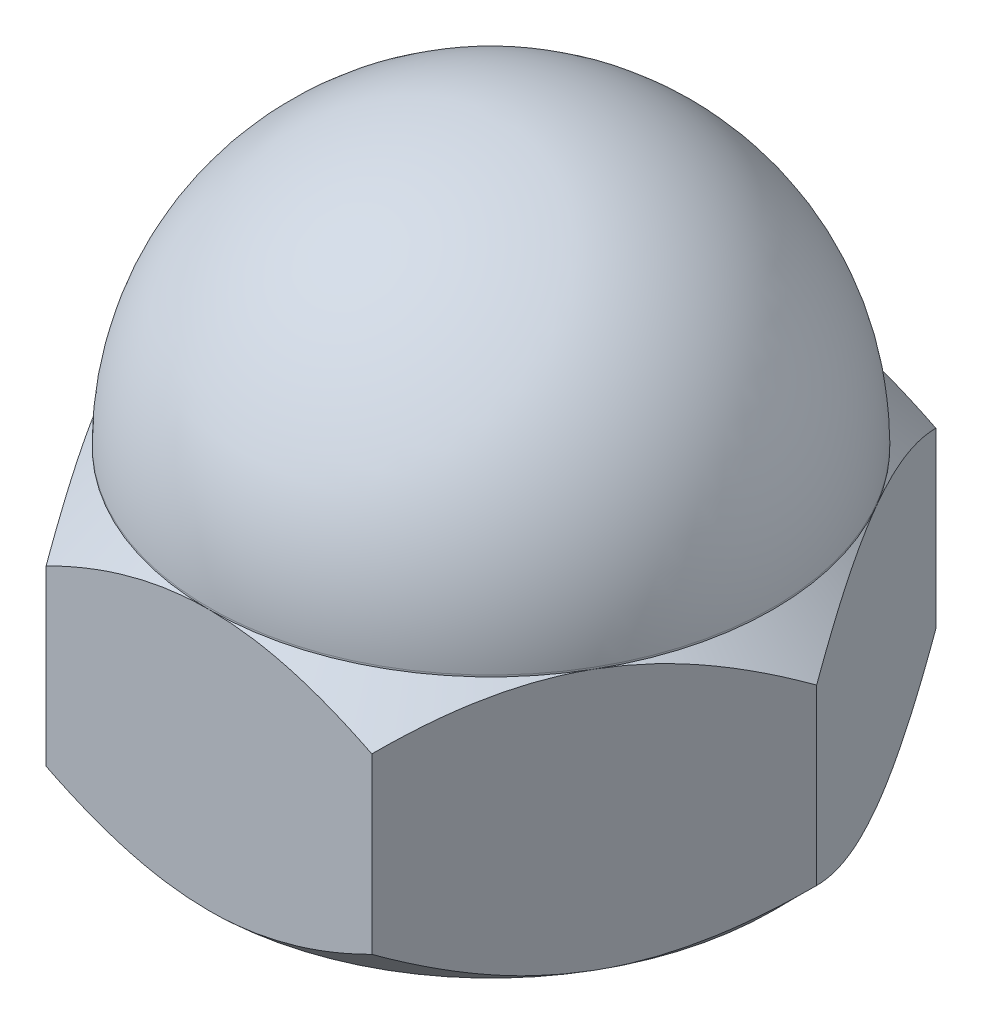
SolidWorks part; units mm, degrees
material "1023 Carbon Steel Sheet (SS)"
ref_plane "Front Plane" through (0, 0, 0) normal (0, 0, 1) x (1, 0, 0)
ref_plane "Top Plane" through (0, 0, 0) normal (0, 1, 0) x (1, 0, 0)
ref_plane "Right Plane" through (0, 0, 0) normal (1, 0, 0) x (0, 0, -1)
sketch "Sketch1" plane through (0, 0, 0) normal (0, 1, 0) x (1, 0, 0)
  line L1 (19.975, 0) -> (9.9875, 17.2989)
  line L2 (9.9875, 17.2989) -> (-9.9875, 17.2989)
  line L3 (-9.9875, 17.2989) -> (-19.975, 0)
  line L4 (-19.975, 0) -> (-9.9875, -17.2989)
  line L5 (-9.9875, -17.2989) -> (9.9875, -17.2989)
  line L6 (9.9875, -17.2989) -> (19.975, 0)
  circle A0 centre (0, 0) radius 17.2989 construction
  dimension "D1" = 39.95
extrude "Boss-Extrude1" add sketch "Sketch1" along normal blind 16 contours L2 L3 L4 L5 L6 L1
sketch "Sketch2" plane through (0, 0, 0) normal (-1, 0, 0) x (0, 0, 1)
  line L2 (-17.2989, 16) -> (-17.2989, 16.1011)
  line L3 (0, 16) -> (17.2989, 16) construction
  line L4 (-17.2989, 16) -> (0, 16)
  line L6 (0, 16) -> (0, 33.4)
  arc A0 (-17.2989, 16.1011) -> (0, 33.4) centre (0, 16.1011) cw
  dimension "D2" = 33.4
revolve "Revolve1" add sketch "Sketch2" angle 360 about L6
hole_wizard "Ø1.0mm Dowel Hole1" positions "Sketch4" profile "Sketch5" hole size "Ø1.0" standard "ISO"
sketch "Sketch4" plane through (0, 0, 0) normal (0, -1, 0) x (-1, 0, 0)
  point P0 (0, 0)
sketch "Sketch5" plane through (0, 0, 0) normal (1, 0, 0) x (0, 0, -1)
  line L0 (0, 0) -> (0, 32.4086)
  line L1 (0, 32.4086) -> (10, 26.4)
  line L2 (10, 26.4) -> (10, 0)
  line L5 (10, 0) -> (0, 0)
  line L10 (0, 32.4086) -> (-10, 26.4) construction
  line L11 (0, -6.35) -> (0, 107.95) construction
  dimension "Hole Dia." = 20
  dimension "Hole Depth" = 26.4
  dimension "Drill Angle" = 118
sketch "Sketch6" plane through (0, 0, 0) normal (0, 0, 1) x (1, 0, 0)
  line L0 (17.2989, 16) -> (19.975, 13.3239)
  line L1 (19.975, 16) -> (19.975, 0) construction
  line L2 (19.975, 13.3239) -> (19.975, 16)
  line L3 (19.975, 16) -> (17.2989, 16)
  line L4 (-19.975, 16) -> (-19.975, 0) construction
  line L5 (-1019.975, 8) -> (48980.025, 8) construction
  line L6 (19.975, 2.6761) -> (19.975, 0)
  line L7 (19.975, 0) -> (17.2989, 0)
  line L8 (17.2989, 0) -> (19.975, 2.6761)
  point P5 (-19.975, 8)
  dimension "D1" = 45
revolve "Cut-Revolve1" cut sketch "Sketch6" angle 360
